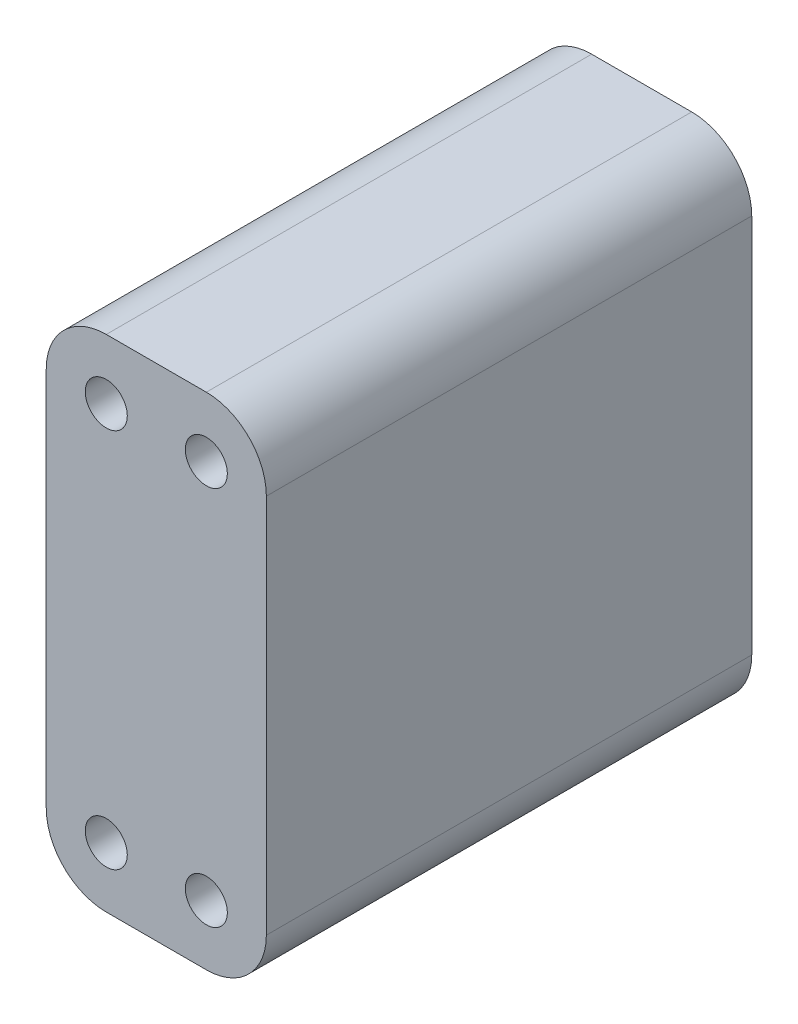
SolidWorks part; units mm, degrees
ref_plane "Plan de face" through (0, 0, 0) normal (0, 0, 1) x (1, 0, 0)
ref_plane "Plan de dessus" through (0, 0, 0) normal (0, 1, 0) x (1, 0, 0)
ref_plane "Plan de droite" through (0, 0, 0) normal (1, 0, 0) x (0, 0, -1)
sketch "Esquisse1" plane through (0, 0, 0) normal (0, 0, 1) x (1, 0, 0)
  line L5 (-11, 25) -> (11, 25)
  line L6 (-11, 25) -> (-11, -25)
  line L7 (-11, -25) -> (11, -25)
  line L8 (11, 25) -> (11, -25)
  point P4 (11, 0)
  point P5 (0, -25)
  dimension "D1" = 50
  dimension "D2" = 22
extrude "Boss.-Extru.1" add sketch "Esquisse1" along normal blind 48.514
fillet "Congé1" radius 6 4 edges at (11, 25, 24.257) (-11, 25, 24.257) (-11, -25, 24.257) (11, -25, 24.257)
ref_plane "milieu" through (0, 0, 24.257) normal (0, 0, 1) x (1, 0, 0)
sketch "Esquisse2" plane through (0, 0, 48.514) normal (0, 0, 1) x (1, 0, 0)
  circle A0 centre (-5, 19) radius 2.1
  circle A1 centre (5, 19) radius 2.1
  circle A2 centre (-5, -19) radius 2.1
  circle A3 centre (5, -19) radius 2.1
  arc A4 (5, -25) -> (11, -19) centre (5, -19) ccw construction
  arc A5 (-11, -19) -> (-5, -25) centre (-5, -19) ccw construction
  arc A6 (-5, 25) -> (-11, 19) centre (-5, 19) ccw construction
  point P8 (5.1573, -19.1298)
  dimension "D1" = 4.2
extrude "Enlèv. mat.-Extru.1" cut sketch "Esquisse2" against normal through all
